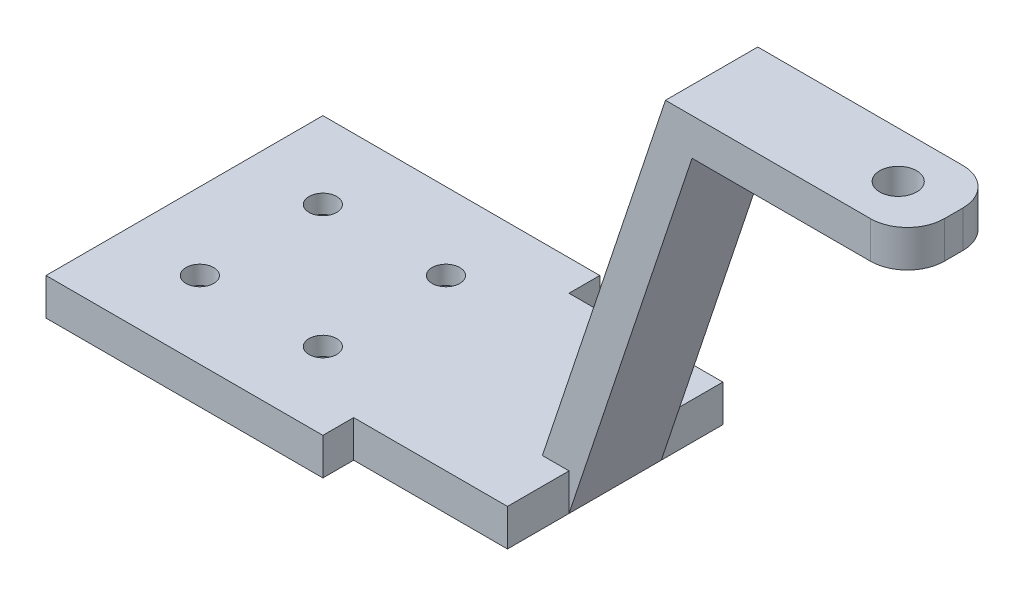
SolidWorks part; units mm, degrees
material "Pure Gold"
ref_plane "Front Plane" through (0, 0, 0) normal (0, 0, 1) x (1, 0, 0)
ref_plane "Top Plane" through (0, 0, 0) normal (0, 1, 0) x (1, 0, 0)
ref_plane "Right Plane" through (0, 0, 0) normal (1, 0, 0) x (0, 0, -1)
sketch "Sketch1" plane through (0, 0, 0) normal (0, 1, 0) x (1, 0, 0)
  line L1 (-22.5, -22.5) -> (22.5, -22.5)
  line L2 (-22.5, -22.5) -> (-22.5, 22.5)
  line L3 (-22.5, 22.5) -> (22.5, 22.5)
  line L4 (22.5, -22.5) -> (22.5, 22.5)
  line L5 (-22.5, -22.5) -> (22.5, 22.5) construction
  line L6 (-22.5, 22.5) -> (22.5, -22.5) construction
  point P0 (0, 0)
  dimension "D1" = 45
  dimension "D2" = 45
extrude "BASE" add sketch "Sketch1" against normal blind 6
hole_wizard "CBORE for M4 Hex Head Machine Screw1" positions "Sketch3" profile "Sketch2" counterbore size "M4" standard "ANSI Metric" end condition through all
sketch "Sketch3" plane through (0, -6, 0) normal (0, -1, 0) x (-1, 0, 0)
  point P0 (10, -10)
  point P2 (-10, -10)
  point P4 (-10, 10)
  point P6 (10, 10)
  dimension "D1" = 10
  dimension "D4" = 10
  dimension "D2" = 10
  dimension "D3" = 10
  dimension "D5" = 10
  dimension "D6" = 10
  dimension "D7" = 10
  dimension "D8" = 10
sketch "Sketch2" plane through (-10, -6, 10) normal (1, 0, 0) x (0, 0, -1)
  line L0 (0, 0) -> (0, 6)
  line L1 (0, 6) -> (2.25, 6)
  line L3 (2.25, 6) -> (2.25, 3)
  line L4 (2.25, 3) -> (5.295, 3)
  line L5 (5.295, 3) -> (5.295, 0)
  line L7 (5.295, 0) -> (0, 0)
  line L11 (0, -6.35) -> (0, 107.95) construction
  dimension "Thru Hole Dia." = 4.5
  dimension "Thru Hole Depth" = 6
  dimension "C'Bore Dia." = 10.59
  dimension "C'Bore Depth" = 3
sketch "Sketch4" plane through (22.5, 0, 0) normal (1, 0, 0) x (0, 0, -1)
  line L0 (-22.5, 0) -> (22.5, 0) construction
  line L1 (-17.5, 0) -> (17.5, 0)
  line L2 (-17.5, 0) -> (-17.5, -6)
  line L3 (-17.5, -6) -> (17.5, -6)
  line L4 (17.5, 0) -> (17.5, -6)
  line L5 (-17.5, 0) -> (17.5, -6) construction
  line L6 (-17.5, -6) -> (17.5, 0) construction
  line L7 (-22.5, -6) -> (22.5, -6) construction
  point P4 (0, -3)
  point P9 (0, 0)
  dimension "D1" = 35
  dimension "D2" = 17.5
extrude "Standing Platform" add sketch "Sketch4" along normal blind 25
sketch "Sketch5" plane through (0, 0, 0) normal (0, 0, 1) x (1, 0, 0)
  line L0 (47.5, -6) -> (67.5, 54)
  line L1 (67.5, 54) -> (102.5, 54)
  line L2 (102.5, 54) -> (102.5, 60)
  line L3 (102.5, 60) -> (63.1754, 60)
  line L4 (63.1754, 60) -> (41.1754, -6)
  line L7 (47.5, -6) -> (22.5, -6) construction
  line L8 (47.5, -6) -> (41.1754, -6)
  point P8 (41.5535, -6)
  point P9 (0, 0)
  point P11 (0, 0)
  point P12 (47.5, 10.8737)
  point P14 (0, 0)
  point P15 (45.0086, -6)
  point P16 (47.5, 8.0849)
  dimension "D1" = 60
  dimension "D2" = 6
  dimension "D3" = 20
  dimension "D4" = 6
  dimension "D5" = 55
extrude "Front Arm" add sketch "Sketch5" along normal mid plane 15
sketch "Sketch6" plane through (0, 60, 0) normal (0, 1, 0) x (1, 0, 0)
  line L0 (102.5, -7.5) -> (102.5, 7.5) construction
  circle A0 centre (93.5, 0) radius 3
  dimension "D1" = 6
  dimension "D2" = 9
extrude "Steering Hole" cut sketch "Sketch6" against normal blind 15
fillet "Fillet1" radius 6 2 edges at (102.5, 57, -7.5) (102.5, 57, 7.5)
equation "\"D2@Sketch3\"=\"D1@Sketch3\""
equation "\"D3@Sketch3\"=\"D1@Sketch3\""
equation "\"D4@Sketch3\"=\"D1@Sketch3\""
equation "\"D5@Sketch3\"=\"D1@Sketch3\""
equation "\"D6@Sketch3\"=\"D1@Sketch3\""
equation "\"D7@Sketch3\"=\"D1@Sketch3\""
equation "\"D8@Sketch3\"=\"D1@Sketch3\""
